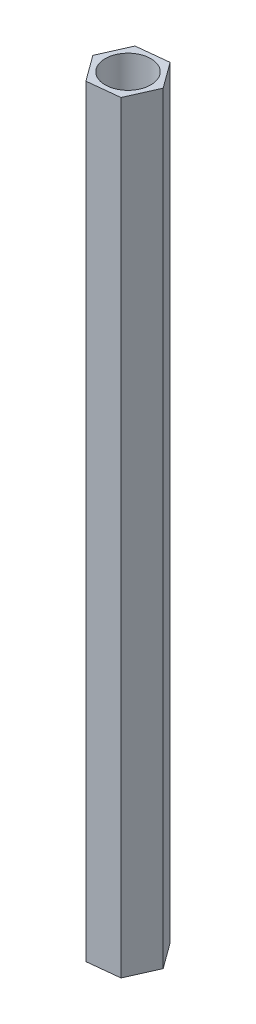
SolidWorks part; units mm, degrees
ref_plane "Front Plane" through (0, 0, 0) normal (0, 0, 1) x (1, 0, 0)
ref_plane "Top Plane" through (0, 0, 0) normal (0, 1, 0) x (1, 0, 0)
ref_plane "Right Plane" through (0, 0, 0) normal (1, 0, 0) x (0, 0, -1)
sketch "Sketch1" plane through (0, 0, 0) normal (0, 1, 0) x (1, 0, 0)
  line L1 (1.3617, -1.8652) -> (2.2962, 0.2466)
  line L2 (2.2962, 0.2466) -> (0.9345, 2.1119)
  line L3 (0.9345, 2.1119) -> (-1.3617, 1.8652)
  line L4 (-1.3617, 1.8652) -> (-2.2962, -0.2466)
  line L5 (-2.2962, -0.2466) -> (-0.9345, -2.1119)
  line L6 (-0.9345, -2.1119) -> (1.3617, -1.8652)
  circle A0 centre (0, 0) radius 2 construction
  circle A1 centre (0, 0) radius 1.65
  dimension "D1" = 4
  dimension "D2" = 3.3
extrude "Boss-Extrude1" add sketch "Sketch1" along normal blind 55.15
